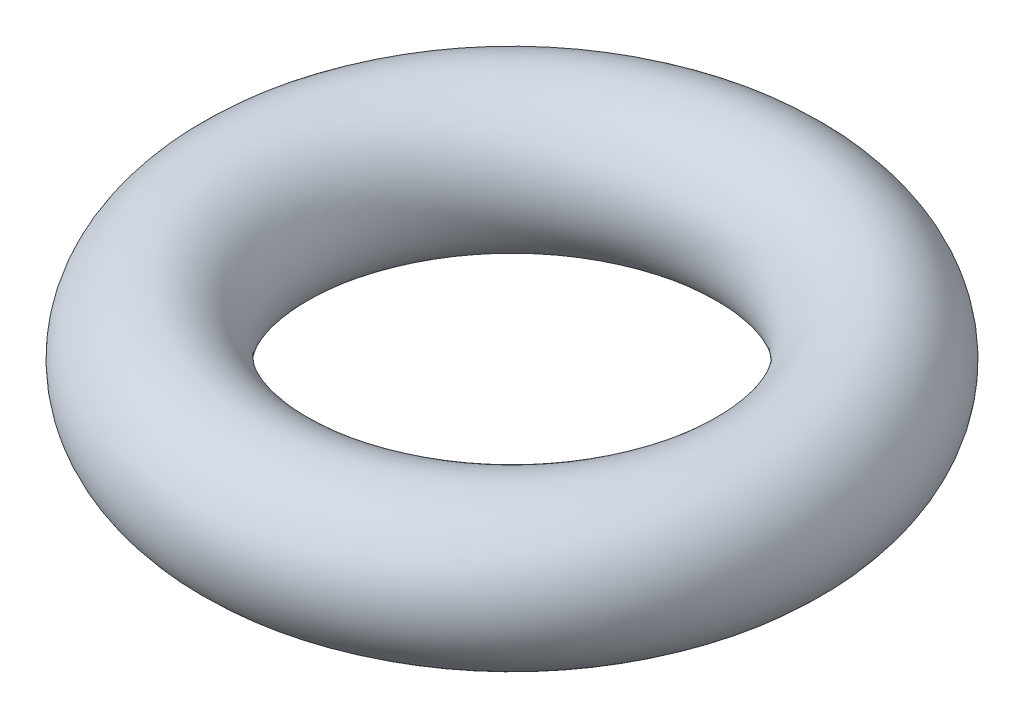
SolidWorks part; units mm, degrees
ref_plane "Front" through (0, 0, 0) normal (0, 0, 1) x (1, 0, 0)
ref_plane "Top" through (0, 0, 0) normal (0, 1, 0) x (1, 0, 0)
ref_plane "Right" through (0, 0, 0) normal (1, 0, 0) x (0, 0, -1)
sketch "Sketch1" plane through (0, 0, 0) normal (0, 0, 1) x (1, 0, 0)
  line L0 (0, 0) -> (0, 1.574) construction
  line L1 (2.5, -1.574) -> (2.5, 1.574) construction
  line L2 (4.5, -1.574) -> (4.5, 1.574) construction
  line L3 (4.5, 0) -> (2.5, 0) construction
  circle A0 centre (3.5, 0) radius 1
  point P11 (3.5, 0.8082)
  point P12 (3.5, 1.4978)
  point P13 (0, 0)
  point P14 (0, 0)
  point P15 (2.3121, -1.3383)
  point P16 (0, 1.574)
  point P17 (2.0848, 1.574)
  dimension "D1" = 2.5
  dimension "D2" = 4.5
revolve "Revolve1" add sketch "Sketch1" angle 360 about L0
